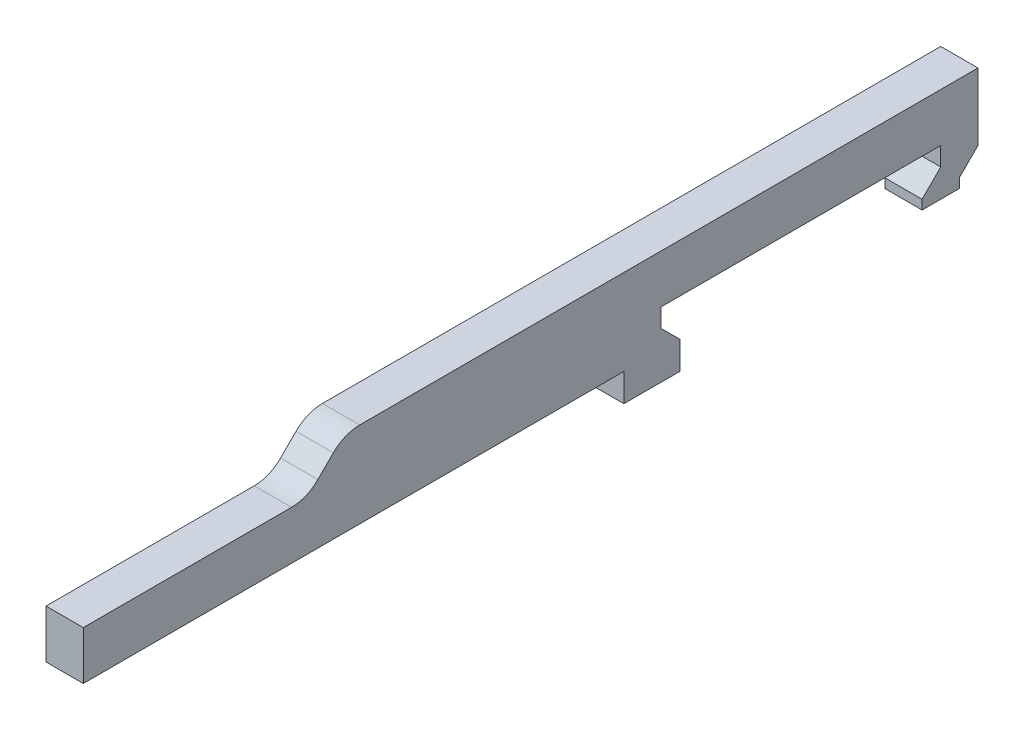
SolidWorks part; units mm, degrees
ref_plane "Спереди" through (0, 0, 0) normal (0, 0, 1) x (1, 0, 0)
ref_plane "Сверху" through (0, 0, 0) normal (0, 1, 0) x (1, 0, 0)
ref_plane "Справа" through (0, 0, 0) normal (1, 0, 0) x (0, 0, -1)
sketch "Эскиз1" plane through (0, 0, 0) normal (1, 0, 0) x (0, 0, -1)
  line L0 (12, 2.6) -> (14, 4.6)
  line L1 (0, 0) -> (12, 0)
  line L2 (0, 0) -> (0, 2.6)
  line L3 (0, 2.6) -> (12, 2.6)
  line L4 (12, 0) -> (12, 2.6)
  line L5 (14, 4.6) -> (14, 2.6) construction
  line L6 (14, 2.6) -> (12, 2.6) construction
  line L7 (14, 4.6) -> (29, 4.6)
  line L8 (12, 0) -> (29, 0)
  line L9 (29, 0) -> (29, -1.5)
  line L10 (29, -1.5) -> (32, -1.5)
  line L11 (32, -1.5) -> (32, 0)
  line L12 (32, 0) -> (31, 1)
  line L13 (31, 1) -> (31, 2)
  line L14 (31, 2) -> (46, 2)
  line L15 (32, 0) -> (31, 0) construction
  line L16 (31, 0) -> (31, 1) construction
  line L17 (38.5, 2) -> (38.5, 1) construction
  line L18 (45, 0) -> (46, 1)
  line L19 (46, 1) -> (46, 2)
  line L20 (45, 0) -> (45, -0.5)
  line L21 (45, -0.5) -> (47, -0.5)
  line L22 (47, -0.5) -> (47, 0)
  line L23 (47, 0) -> (48, 1)
  line L24 (48, 1) -> (48, 4.6)
  line L25 (48, 4.6) -> (29, 4.6)
  dimension "D1" = 2.6
  dimension "D2" = 12
  dimension "D3" = 2
  dimension "D4" = 2
  dimension "D5" = 15
  dimension "D6" = 17
  dimension "D7" = 1.5
  dimension "D8" = 3
  dimension "D9" = 1.5
  dimension "D10" = 1
  dimension "D11" = 1
  dimension "D12" = 1
  dimension "D13" = 15
  dimension "D14" = 0.5
  dimension "D15" = 2
extrude "Бобышка-Вытянуть1" add sketch "Эскиз1" along normal blind 2 contours L24 L25 L7 L0 L4 L8 L9 L10 L11 L12 L13 L14 L19 L18 L20 L21 L22 L23 | L1 L4 L3 L2
fillet "Скругление1" radius 2 2 edges at (1, 4.6, -14) (1, 2.6, -12)
